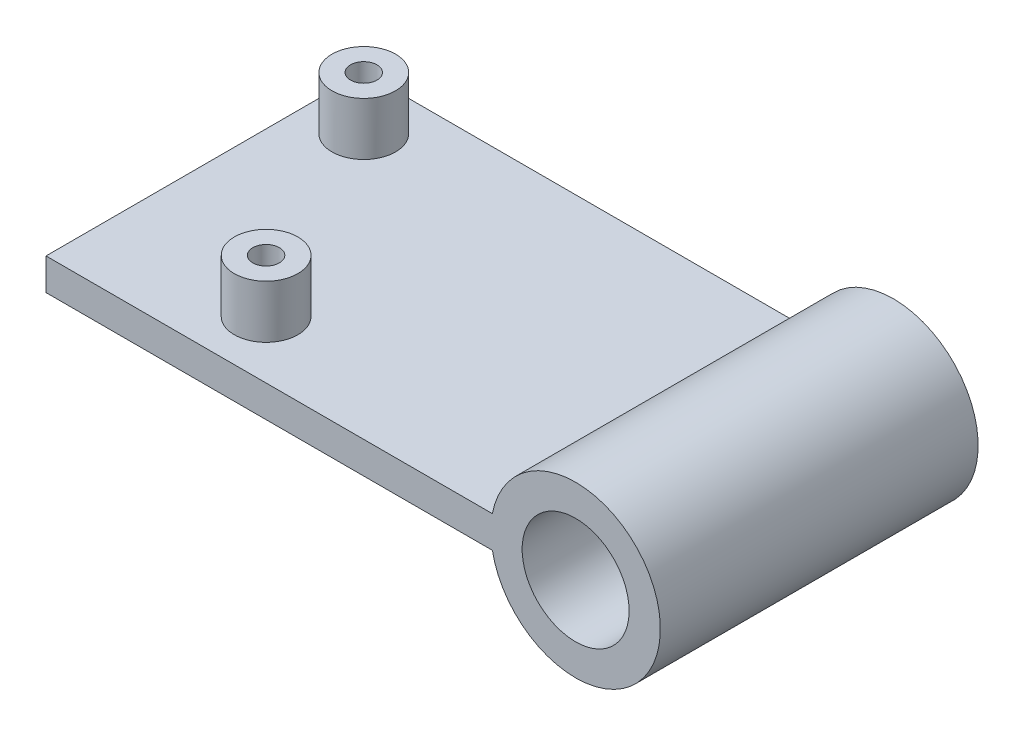
SolidWorks part; units mm, degrees
ref_plane "Front Plane" through (0, 0, 0) normal (0, 0, 1) x (1, 0, 0)
ref_plane "Top Plane" through (0, 0, 0) normal (0, 1, 0) x (1, 0, 0)
ref_plane "Right Plane" through (0, 0, 0) normal (1, 0, 0) x (0, 0, -1)
sketch "Sketch1" plane through (0, 0, 0) normal (0, 0, 1) x (1, 0, 0)
  line L1 (-7.8581, 1.5) -> (-50, 1.5)
  line L2 (-7.8581, -1.5) -> (-50, -1.5)
  line L3 (-50, 1.5) -> (-50, -1.5)
  circle A0 centre (0, 0) radius 5.05
  arc A1 (-7.8581, -1.5) -> (-7.8581, 1.5) centre (0, 0) ccw
extrude "Boss-Extrude1" add sketch "Sketch1" along normal blind 30
sketch "Sketch2" plane through (0, 1.5, 0) normal (0, 1, 0) x (1, 0, 0)
  line L0 (-50, -30) -> (-50, 0) construction
  line L1 (-7.8581, 0) -> (-50, 0) construction
  circle A0 centre (-45, -5) radius 1.25
  circle A1 centre (-45, -5) radius 3
  circle A4 centre (-34.6622, -24.558) radius 3
  circle A5 centre (-34.6622, -24.558) radius 1.25
  circle A8 centre (-34.6622, -5) radius 3 [skipped]
  circle A9 centre (-34.6622, -5) radius 1.25 [skipped]
  circle A10 centre (-45, -24.558) radius 1.25 [skipped]
  circle A11 centre (-45, -24.558) radius 3 [skipped]
  dimension "D1" = 5
  dimension "D2" = 5
  dimension "D5" = 19.558
  dimension "D6" = 10.3378
  dimension "D3" = 2
  dimension "D4" = 2
extrude "Boss-Extrude2" add sketch "Sketch2" along normal blind 5
